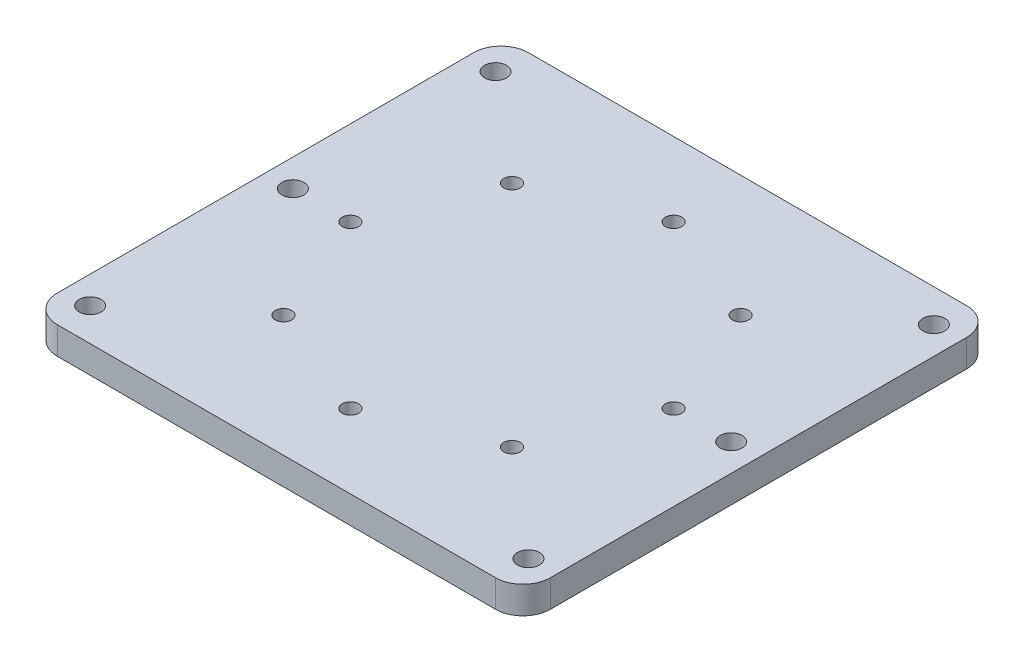
SolidWorks part; units mm, degrees
ref_plane "前视基准面" through (0, 0, 0) normal (0, 0, 1) x (1, 0, 0)
ref_plane "上视基准面" through (0, 0, 0) normal (0, 1, 0) x (1, 0, 0)
ref_plane "右视基准面" through (0, 0, 0) normal (1, 0, 0) x (0, 0, -1)
sketch "草图1" plane through (0, 0, 0) normal (0, 1, 0) x (1, 0, 0)
  line L0 (0, 43) -> (0, -43) construction
  line L1 (-45, 43) -> (45, 43)
  line L2 (-45, 43) -> (-45, -43)
  line L3 (-45, -43) -> (45, -43)
  line L4 (45, 43) -> (45, -43)
  line L5 (-45, 0) -> (45, 0) construction
  circle A0 centre (0, 29.5) radius 1.5
  circle A1 centre (20.8597, 20.8597) radius 1.5
  circle A2 centre (29.5, 0) radius 1.5
  circle A3 centre (20.8597, -20.8597) radius 1.5
  circle A4 centre (0, -29.5) radius 1.5
  circle A5 centre (-20.8597, -20.8597) radius 1.5
  circle A6 centre (-29.5, 0) radius 1.5
  circle A7 centre (-20.8597, 20.8597) radius 1.5
  circle A8 centre (-40, 0) radius 2
  circle A9 centre (40, 0) radius 2
  circle A10 centre (-40, 37) radius 2
  circle A11 centre (40, 37) radius 2
  circle A12 centre (40, -37) radius 2
  circle A13 centre (-40, -37) radius 2
  point P24 (0, 0)
  dimension "D5" = 3
  dimension "D8" = 4
  dimension "D10" = 4
  dimension "D1" = 90
  dimension "D2" = 86
  dimension "D3" = 45
  dimension "D4" = 43
  dimension "D6" = 29.5
  dimension "D9" = 5
  dimension "D11" = 6
  dimension "D7" = 8
extrude "凸台-拉伸1" add sketch "草图1" along normal blind 5
fillet "圆角1" radius 5 4 edges at (-45, 2.5, -43) (45, 2.5, -43) (45, 2.5, 43) (-45, 2.5, 43)
